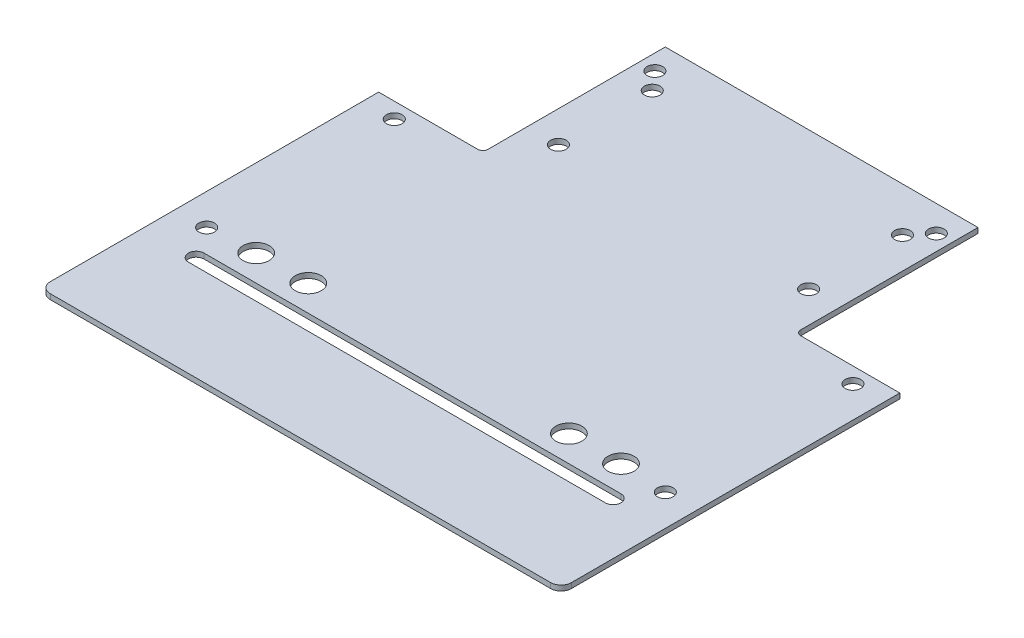
SolidWorks part; units mm, degrees
ref_plane "Front Plane" through (0, 0, 0) normal (0, 0, 1) x (1, 0, 0)
ref_plane "Top Plane" through (0, 0, 0) normal (0, 1, 0) x (1, 0, 0)
ref_plane "Right Plane" through (0, 0, 0) normal (1, 0, 0) x (0, 0, -1)
sketch "Sketch1" plane through (0, 0, 0) normal (0, 1, 0) x (1, 0, 0)
  line L0 (10, 20) -> (90, 20) construction
  line L1 (2, 0) -> (98, 0)
  line L2 (0, 2) -> (0, 98)
  line L3 (2, 100) -> (98, 100)
  line L4 (100, 2) -> (100, 98)
  line L5 (10, 21.5) -> (90, 21.5)
  line L6 (10, 18.5) -> (90, 18.5)
  arc A0 (10, 21.5) -> (10, 18.5) centre (10, 20) ccw
  arc A1 (90, 18.5) -> (90, 21.5) centre (90, 20) ccw
  arc A2 (2, 0) -> (0, 2) centre (2, 2) cw
  arc A3 (98, 0) -> (100, 2) centre (98, 2) ccw
  arc A4 (98, 100) -> (100, 98) centre (98, 98) cw
  arc A5 (0, 98) -> (2, 100) centre (2, 98) cw
  point P7 (50, 20)
  point P14 (0, 0)
  point P17 (100, 0)
  point P20 (100, 100)
  dimension "D7" = 2
  dimension "D1" = 100
  dimension "D2" = 100
  dimension "D3" = 10
  dimension "D4" = 10
  dimension "D5" = 20
  dimension "D6" = 1.5
extrude "Boss-Extrude1" add sketch "Sketch1" along normal blind 1
sketch "Sketch2" plane through (0, 1, 0) normal (0, 1, 0) x (1, 0, 0)
  line L0 (0, 98) -> (0, 2) construction
  line L1 (0, 65) -> (19, 65)
  line L2 (0, 65) -> (0, 100)
  line L3 (0, 100) -> (19, 100)
  line L4 (20, 66) -> (20, 99)
  line L5 (98, 100) -> (2, 100) construction
  line L6 (90, 21.5) -> (10, 21.5) construction
  line L7 (50, 21.5) -> (50, 100) construction
  line L8 (20, 82.5) -> (50, 82.5) construction
  line L9 (100, 100) -> (81, 100)
  line L10 (80, 66) -> (80, 99)
  line L11 (100, 65) -> (81, 65)
  line L12 (100, 65) -> (100, 100)
  line L19 (80, 99) -> (81, 99)
  line L20 (80, 99) -> (80, 100)
  line L21 (80, 100) -> (81, 100)
  line L22 (81, 99) -> (81, 100)
  line L23 (19, 99) -> (20, 99)
  line L24 (19, 99) -> (19, 100)
  line L25 (19, 100) -> (20, 100)
  line L26 (20, 99) -> (20, 100)
  circle A0 centre (26, 91.5) radius 1.5
  circle A1 centre (26, 73.5) radius 1.5
  arc A2 (19, 65) -> (20, 66) centre (19, 66) ccw
  arc A3 (19, 100) -> (20, 99) centre (19, 99) cw
  circle A4 centre (74, 91.5) radius 1.5
  circle A5 centre (74, 73.5) radius 1.5
  arc A6 (81, 100) -> (80, 99) centre (81, 99) ccw
  arc A7 (81, 65) -> (80, 66) centre (81, 66) cw
  circle A8 centre (15, 26.5) radius 2.5
  circle A9 centre (25, 26.5) radius 2.5
  circle A11 centre (85, 26.5) radius 2.5
  circle A12 centre (75, 26.5) radius 2.5
  point P20 (20, 65)
  point P23 (20, 100)
  dimension "D6" = 3
  dimension "D7" = 1
  dimension "D9" = 5
  dimension "D1" = 20
  dimension "D2" = 0
  dimension "D3" = 35
  dimension "D4" = 9
  dimension "D5" = 6
  dimension "D8" = 10
  dimension "D10" = 5
  dimension "D14" = 15
extrude "Cut-Extrude2" cut sketch "Sketch2" against normal blind 1
sketch "Sketch3" plane through (0, 1, 0) normal (0, 1, 0) x (1, 0, 0)
  line L0 (0, 65) -> (0, 2) construction
  line L1 (100, 2) -> (100, 65) construction
  line L2 (80, 66) -> (80, 100) construction
  line L3 (90, 21.5) -> (10, 21.5) construction
  line L4 (80, 100) -> (20, 100) construction
  line L5 (20, 66) -> (20, 100) construction
  line L6 (0, 65) -> (19, 65) construction
  line L7 (100, 65) -> (81, 65) construction
  circle A0 centre (6, 26) radius 1.5
  circle A1 centre (23, 95) radius 1.5
  circle A2 centre (77, 95) radius 1.5
  circle A3 centre (94, 26) radius 1.5
  circle A4 centre (6, 62) radius 1.5
  circle A5 centre (94, 62) radius 1.5
  dimension "D2" = 3
  dimension "D10" = 3
  dimension "D1" = 6
  dimension "D3" = 6
  dimension "D4" = 3
  dimension "D5" = 4.5
  dimension "D6" = 4.5
  dimension "D7" = 5
  dimension "D8" = 5
  dimension "D9" = 3
  dimension "D11" = 3
  dimension "D12" = 3
  dimension "D13" = 6
  dimension "D14" = 6
extrude "Cut-Extrude3" cut sketch "Sketch3" against normal blind 1
